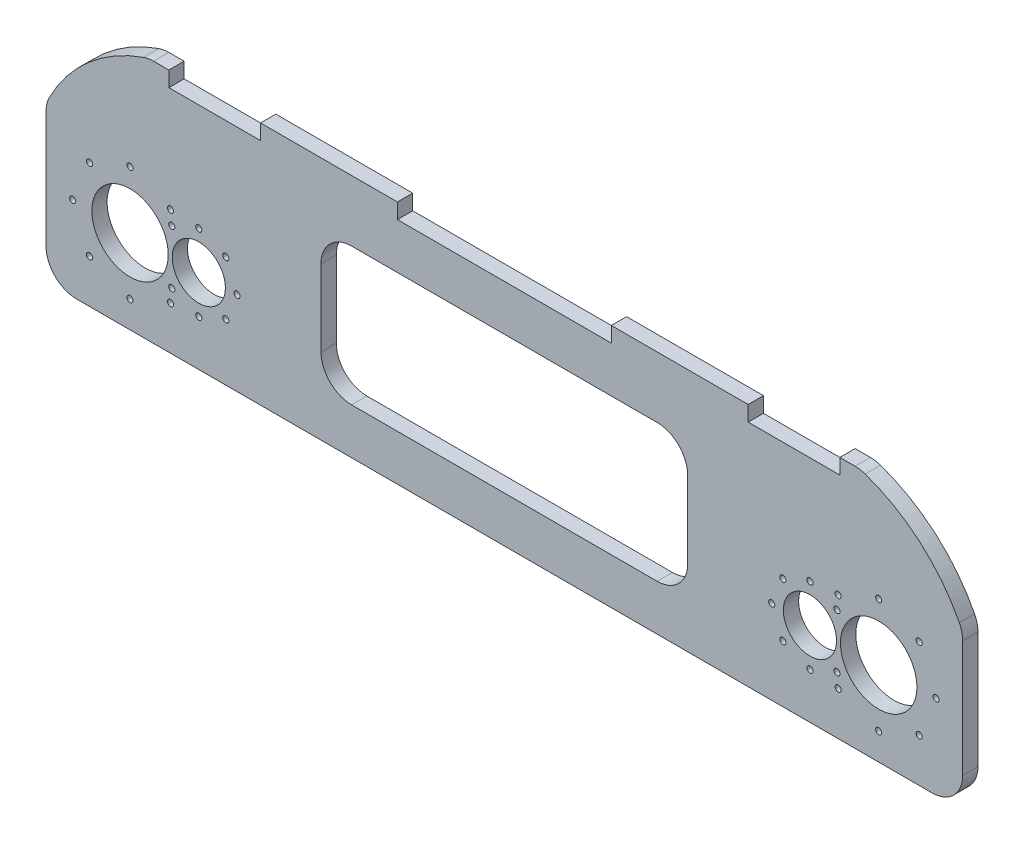
SolidWorks part; units mm, degrees
material "ABS"
ref_plane "Front Plane" through (0, 0, 0) normal (0, 0, 1) x (1, 0, 0)
ref_plane "Top Plane" through (0, 0, 0) normal (0, 1, 0) x (1, 0, 0)
ref_plane "Right Plane" through (0, 0, 0) normal (1, 0, 0) x (0, 0, -1)
sketch "Sketch1" plane through (0, 0, 0) normal (0, 0, 1) x (1, 0, 0)
  line L0 (-145.7836, 66.675) -> (145.7836, 66.675)
  line L1 (-190.5, 26.1817) -> (-190.5, -22.225)
  line L4 (0, 0) -> (0, 100.7987) construction
  line L5 (-177.8, -34.925) -> (177.8, -34.925)
  line L6 (190.5, 26.1817) -> (190.5, -22.225)
  line L7 (-190.5, 34.925) -> (190.5, -34.925) construction
  line L8 (-190.5, -34.925) -> (190.5, 34.925) construction
  arc A0 (177.8, -34.925) -> (190.5, -22.225) centre (177.8, -22.225) ccw
  arc A1 (149.9577, 65.9694) -> (189.0889, 31.9999) centre (127, 0) cw
  circle A2 centre (-127, 0) radius 3.175
  circle A3 centre (127, 0) radius 3.175
  arc A4 (-177.8, -34.925) -> (-190.5, -22.225) centre (-177.8, -22.225) cw
  arc A5 (190.5, 26.1817) -> (189.0889, 31.9999) centre (177.8, 26.1817) ccw
  arc A6 (-149.9577, 65.9694) -> (-189.0889, 31.9999) centre (-127, 0) ccw
  arc A7 (149.9577, 65.9694) -> (145.7836, 66.675) centre (145.7836, 53.975) ccw
  arc A8 (-190.5, 26.1817) -> (-189.0889, 31.9999) centre (-177.8, 26.1817) cw
  arc A9 (-145.7836, 66.675) -> (-149.9577, 65.9694) centre (-145.7836, 53.975) ccw
  point P0 (0, 0)
  point P22 (190.5, 29.0994)
  point P27 (147.8199, 66.675)
  point P30 (-190.5, 29.0994)
  point P33 (-147.8199, 66.675)
  dimension "D3" = 6.35
  dimension "D4" = 6.35
  dimension "D6" = 66.675
  dimension "D7" = 12.7
  dimension "D2" = 381
  dimension "D5" = 12.7
  dimension "D1" = 69.85
  dimension "D8" = 139.7
extrude "Boss-Extrude1" add sketch "Sketch1" along normal mid plane 6.35
sketch "Sketch2" plane through (0, 0, 3.175) normal (0, 0, 1) x (1, 0, 0)
  line L0 (-127, 0) -> (-207.737, 0) construction
  line L4 (0, 0) -> (0, 93.9723) construction
  circle A0 centre (-127, 0) radius 11.049
  circle A1 centre (-155.575, 0) radius 15.875
  circle A2 centre (127, 0) radius 15.875 construction
  circle A3 centre (155.575, 0) radius 23.8125 construction
  circle A4 centre (-155.575, 0) radius 23.8125 construction
  circle A5 centre (-127, 0) radius 15.875 construction
  circle A6 centre (-155.575, 23.8125) radius 1.27
  circle A7 centre (-138.737, 16.838) radius 1.27
  circle A8 centre (-131.7625, 0) radius 1.27 [skipped]
  circle A9 centre (-138.737, -16.838) radius 1.27
  circle A10 centre (-155.575, -23.8125) radius 1.27
  circle A11 centre (-172.413, -16.838) radius 1.27
  circle A12 centre (-179.3875, 0) radius 1.27
  circle A13 centre (-172.413, 16.838) radius 1.27
  circle A14 centre (-127, 15.875) radius 1.27
  circle A15 centre (-115.7747, 11.2253) radius 1.27
  circle A16 centre (-111.125, 0) radius 1.27
  circle A17 centre (-115.7747, -11.2253) radius 1.27
  circle A18 centre (-127, -15.875) radius 1.27
  circle A19 centre (-138.2253, -11.2253) radius 1.27
  circle A20 centre (138.2253, 11.2253) radius 1.27
  circle A21 centre (-138.2253, 11.2253) radius 1.27
  circle A22 centre (-142.875, 0) radius 1.27 [skipped]
  circle A23 centre (138.2253, -11.2253) radius 1.27
  circle A24 centre (127, -15.875) radius 1.27
  circle A25 centre (115.7747, -11.2253) radius 1.27
  circle A26 centre (111.125, 0) radius 1.27
  circle A27 centre (115.7747, 11.2253) radius 1.27
  circle A28 centre (127, 15.875) radius 1.27
  circle A29 centre (172.413, 16.838) radius 1.27
  circle A30 centre (179.3875, 0) radius 1.27
  circle A31 centre (172.413, -16.838) radius 1.27
  circle A32 centre (155.575, -23.8125) radius 1.27
  circle A33 centre (138.737, -16.838) radius 1.27
  circle A34 centre (138.737, 16.838) radius 1.27
  circle A35 centre (155.575, 23.8125) radius 1.27
  circle A36 centre (155.575, 0) radius 15.875
  circle A37 centre (127, 0) radius 11.049
  dimension "D2" = 28.575
  dimension "D3" = 31.75
  dimension "D4" = 31.75
  dimension "D5" = 47.625
  dimension "D6" = 2.54
  dimension "D1" = 22.098
  dimension "D8" = 2.54
  dimension "D7" = 8
  dimension "D9" = 8
extrude "Cut-Extrude1" cut sketch "Sketch2" against normal through all
sketch "Sketch3" plane through (0, 0, 3.175) normal (0, 0, 1) x (1, 0, 0)
  line L0 (0, 0) -> (0, 109.3078) construction
  line L1 (145.7836, 66.675) -> (-145.7836, 66.675) construction
  line L2 (-101.3336, 66.675) -> (-139.4336, 66.675)
  line L3 (-101.3336, 66.675) -> (-101.3336, 60.325)
  line L4 (-101.3336, 60.325) -> (-139.4336, 60.325)
  line L5 (-139.4336, 66.675) -> (-139.4336, 60.325)
  line L6 (139.4336, 66.675) -> (139.4336, 60.325)
  line L7 (101.3336, 60.325) -> (139.4336, 60.325)
  line L8 (101.3336, 66.675) -> (101.3336, 60.325)
  line L9 (101.3336, 66.675) -> (139.4336, 66.675)
  line L11 (44.45, 60.325) -> (-44.45, 60.325)
  line L12 (44.45, 60.325) -> (44.45, 66.675)
  line L13 (44.45, 66.675) -> (-44.45, 66.675)
  line L14 (-44.45, 60.325) -> (-44.45, 66.675)
  line L15 (44.45, 60.325) -> (-44.45, 66.675) construction
  line L16 (44.45, 66.675) -> (-44.45, 60.325) construction
  point P13 (0, 63.5)
  dimension "D1" = 6.35
  dimension "D2" = 38.1
  dimension "D3" = 6.35
  dimension "D4" = 6.35
  dimension "D5" = 88.9
extrude "Cut-Extrude4" cut sketch "Sketch3" against normal through all
sketch "Sketch4" plane through (0, 0, 3.175) normal (0, 0, 1) x (1, 0, 0)
  line L0 (0, 93.6628) -> (0, -75.0769) construction
  line L1 (101.3336, 66.675) -> (44.45, 66.675) construction
  line L2 (-63.5, 41.275) -> (63.5, 41.275)
  line L3 (-76.2, 28.575) -> (-76.2, -3.175)
  line L4 (-63.5, -15.875) -> (63.5, -15.875)
  line L5 (76.2, 28.575) -> (76.2, -3.175)
  line L6 (-76.2, 41.275) -> (76.2, -15.875) construction
  line L7 (-76.2, -15.875) -> (76.2, 41.275) construction
  line L8 (-177.8, -34.925) -> (177.8, -34.925) construction
  arc A0 (63.5, 41.275) -> (76.2, 28.575) centre (63.5, 28.575) cw
  arc A1 (76.2, -3.175) -> (63.5, -15.875) centre (63.5, -3.175) cw
  arc A2 (-63.5, -15.875) -> (-76.2, -3.175) centre (-63.5, -3.175) cw
  arc A3 (-63.5, 41.275) -> (-76.2, 28.575) centre (-63.5, 28.575) ccw
  point P2 (0, 12.7)
  dimension "D4" = 12.7
  dimension "D1" = 25.4
  dimension "D2" = 19.05
  dimension "D3" = 152.4
extrude "Cut-Extrude5" cut sketch "Sketch4" against normal through all
